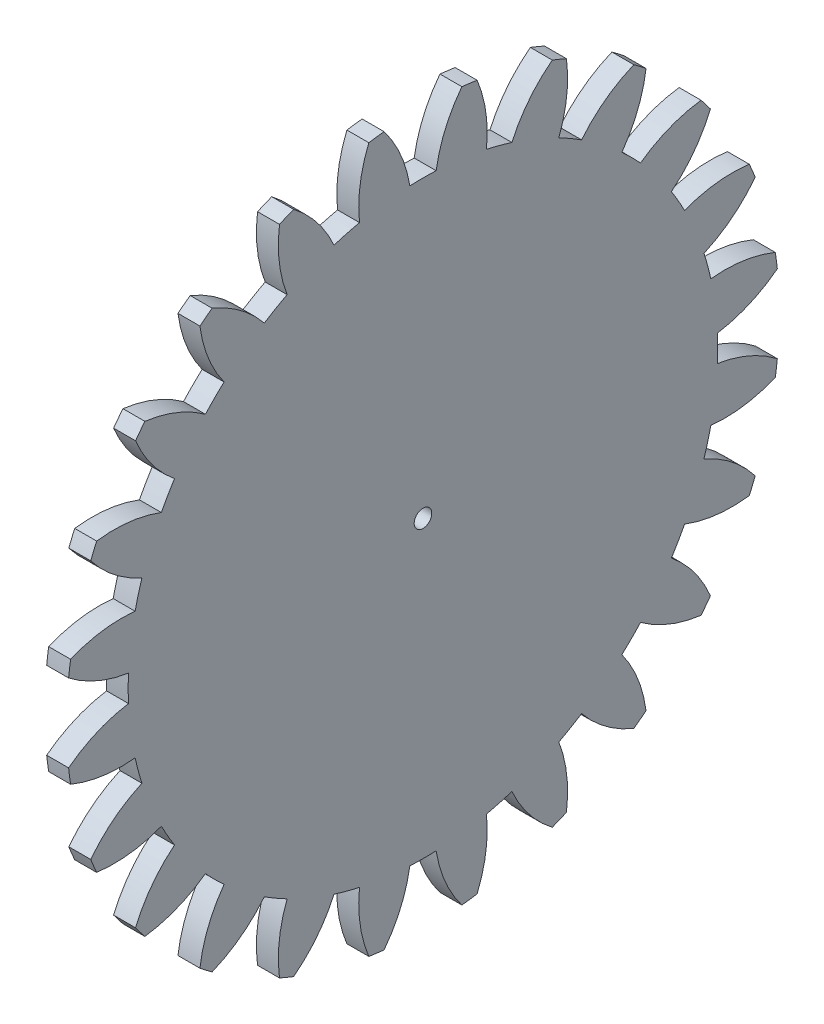
SolidWorks part; units mm, degrees
ref_plane "Plane1" through (0, 0, 0) normal (0, 0, 1) x (1, 0, 0)
ref_plane "Plane2" through (0, 0, 0) normal (0, 1, 0) x (1, 0, 0)
ref_plane "Plane3" through (0, 0, 0) normal (1, 0, 0) x (0, 0, -1)
sketch "HoldingSke" plane through (0, 0, 0) normal (0, 1, 0) x (1, 0, 0)
  line L0 (0, 0) -> (0.7308, -0.3254)
  line L1 (-15, 0) -> (100, 0) construction
  line L2 (0, 0) -> (-2.1039, 2.3779)
  line L3 (0, 0) -> (-11.863, 4.5341)
  line L4 (0, 0) -> (7.8894, 3.5126)
  line L5 (0, 0) -> (-46.8476, -17.4728)
  line L6 (0, 0) -> (-0.829, -0.5593)
  line L7 (-2.1039, 2.3779) -> (8.6587, 51.2062)
  line L8 (-76.2, 54.61) -> (-76.1, 54.61)
  line L9 (-71.009, 38.7566) -> (-53.1078, 45.2721)
  line L10 (-76.2, 71.12) -> (104.1128, 71.12)
  line L11 (0, 0) -> (-1, 0)
  line L12 (-76.2, 101.6) -> (-76.155, 101.6)
  line L13 (24.9733, 27.94) -> (52.9518, 28.4284)
  line L14 (24.9733, 27.94) -> (24.9743, 27.94)
  line L15 (24.9733, 27.94) -> (100.4006, 29.5858)
  line L16 (-63.627, -1.25) -> (-12.827, -1.25)
  circle A0 centre (0, 0) radius 0.4
  circle A1 centre (0, 0) radius 13.4365
  circle A2 centre (0, 0) radius 37.5
  circle A3 centre (0, 0) radius 0.4
  dimension "MHD" = 26.873
  dimension "Hub_dia" = 75
  dimension "Bore" = 0.8
  dimension "MBD" = 0.8
  dimension "Num_teeth" = 24
  dimension "Pitch" = 0.8
  dimension "Overall_len" = 50
  dimension "Show_teeth" = 24
  dimension "Thickness" = 1
  dimension "OAL" = 50.0004
  dimension "T_dim" = 0.1
  dimension "Ap" = 20
  dimension "H" = 19.05
  dimension "Pitch_radius" = 180.3128
  dimension "Width" = 1
  dimension "Backlash" = 0.045
  dimension "Addendum_fac" = 1
  dimension "Dedendum_fac" = 1.25
  dimension "Clearance_fac" = 0.25
  dimension "Dedendum_add" = 0.001
  dimension "Module" = 1.25
sketch "BasProSke" plane through (0, 0, 0) normal (0, 1, 0) x (1, 0, 0)
  line L0 (-10, 0) -> (60, 0) construction
  line L1 (0, 0) -> (0, 16.25)
  line L2 (0, 0) -> (1, 0)
  line L3 (1, 0) -> (1, 16.25)
  line L4 (1, 16.25) -> (0, 16.25)
  dimension "Thickness" = 1
  dimension "Diameter" = 32.5
revolve "Base-Revolve" add sketch "BasProSke" angle 360 about L0
sketch "TooCutSke" plane through (0, 0, 0) normal (1, 0, 0) x (0, 0, -1)
  line L1 (0, 0) -> (0, 107) construction
  line L2 (0, 0) -> (-1.0598, 14.9625) construction
  line L3 (0, 0) -> (-3.9087, 29.6895) construction
  line L4 (-1.0598, 14.9625) -> (-1.9543, 14.8447) construction
  arc A0 (0.6004, 13.4231) -> (-0.6004, 13.4231) centre (0, 0) ccw
  arc A1 (1.7918, 16.1765) -> (-1.7918, 16.1765) centre (0, 0) ccw
  circle A2 centre (0, 0) radius 15 construction
  circle A3 centre (0, 0) radius 14.0954 construction
  arc A4 (-0.6004, 13.4231) -> (-1.7918, 16.1765) centre (-6.5279, 12.4927) ccw
  arc A5 (1.7918, 16.1765) -> (0.6004, 13.4231) centre (6.5279, 12.4927) ccw
  dimension "Root_dia" = 26.873
  dimension "Overcut_dia" = 32.5508
  dimension "Pitch_dia" = 30
  dimension "Base_dia" = 28.1908
  dimension "Flank_rad" = 6
  dimension "Half_ang" = 7.5
  dimension "Half_CT" = 0.9023
extrude "ToothCut" cut sketch "TooCutSke" along normal through all
fillet "Breaks" [suppressed] radius 0.025
fillet "RootFillets" [suppressed] radius 0.3135
pattern_circular "TeethCuts" count 24 over 360 about axis through (0, 0, 0) along (1, 0, 0) of "ToothCut", "RootFillets", "Breaks"
sketch "HubNeaOneSke" plane through (0, 0, 0) normal (-1, 0, 0) x (0, 0, 1)
  circle A0 centre (0, 0) radius 13.4365
  dimension "Diameter" = 26.873
extrude "HubNearOne" [suppressed] add sketch "HubNeaOneSke" along normal blind 49.0004
sketch "HubNeaBotSke" plane through (0, 0, 0) normal (-1, 0, 0) x (0, 0, 1)
  circle A0 centre (0, 0) radius 13.4365
  dimension "Diameter" = 26.873
extrude "HubNearBoth" [suppressed] add sketch "HubNeaBotSke" along normal blind 24.5002
ref_plane "FarPln" through (1, 0, 0) normal (1, 0, 0) x (0, 0, -1)
sketch "HubFarSke" plane through (1, 0, 0) normal (1, 0, 0) x (0, 0, -1)
  circle A0 centre (0, 0) radius 13.4365
  dimension "Diameter" = 26.873
extrude "HubFar" [suppressed] add sketch "HubFarSke" along normal blind 24.5002
sketch "BorSke" plane through (0, 0, 0) normal (1, 0, 0) x (0, 0, -1)
  circle A0 centre (0, 0) radius 0.4
  dimension "Diameter" = 0.8
extrude "Bore" cut sketch "BorSke" along normal mid plane 100.0007
sketch "KeySke" plane through (0, 0, 0) normal (1, 0, 0) x (0, 0, -1)
  line L0 (-0.05, 0) -> (-0.05, 0.5)
  line L1 (-0.05, 0.5) -> (0.05, 0.5)
  line L2 (0.05, 0.5) -> (0.05, 0)
  line L3 (0, 0) -> (0, 34) construction
  line L4 (-0.05, 0) -> (0.05, 0)
  dimension "Offset" = 0.5
extrude "Keyway" [suppressed] cut sketch "KeySke" along normal mid plane 100.0007
pattern_circular "Keyway2" [suppressed] count 2 every 90 about axis through (-10, 0, 0) along (1, 0, 0)
equation "' \"Module@HoldingSke\" = 6.35"
equation "' \"Num_teeth@HoldingSke\" = 12"
equation "' \"Ap@HoldingSke\" =  20"
equation "' \"Ap@HoldingSke\" = 20"
equation "' \"Width@HoldingSke\" = 0.5 * 25.4"
equation "'\"Hub_dia@HoldingSke\"= 1 * 25.4"
equation "'\"Hub_dia@HoldingSke\" = 1 * 25.4"
equation "' \"Overall_len@HoldingSke\" = 1.0 * 25.4"
equation "'\"Bore@HoldingSke\" = 0.5"
equation "' \"T_dim@HoldingSke\" = 0.1 * 25.4"
equation "' \"Width@KeySke\" = 0.25 * 25.4"
equation "' \"Show_teeth@HoldingSke\" = 13"
equation "' \"Backlash@HoldingSke\" = 0.009 * 25.4"
equation "' \"Addendum_fac@HoldingSke\" = 1.0"
equation "' \"Dedendum_fac@HoldingSke\" = 1.25"
equation "' \"Dedendum_add@HoldingSke\" = 0.00005 * 25.4"
equation "' \"Clearance_fac@HoldingSke\" = 0.25"
equation "\"Pitch@HoldingSke\" = 1 / \"Module@HoldingSke\""
equation "\"Overcut_dia@TooCutSke\" = (\"Num_teeth@HoldingSke\" + 2 * \"Addendum_fac@HoldingSke\") / \"Pitch@HoldingSke\" + 0.002 * 25.4"
equation "\"Pitch_dia@TooCutSke\" = \"Num_teeth@HoldingSke\" / \"Pitch@HoldingSke\""
equation "\"Base_dia@TooCutSke\" = \"Num_teeth@HoldingSke\" / \"Pitch@HoldingSke\" * cos((\"Ap@HoldingSke\"  * 3.14159265 / 180))"
equation "\"Root_dia@TooCutSke\" = (\"Num_teeth@HoldingSke\" + 2) / \"Pitch@HoldingSke\" - 2 * (\"Addendum_fac@HoldingSke\" + \"Dedendum_fac@HoldingSke\") / \"Pitch@HoldingSke\" - \"Dedendum_add@HoldingSke\" * 2"
equation "\"Half_ang@TooCutSke\" = 180 / \"Num_teeth@HoldingSke\""
equation "\"Half_CT@TooCutSke\" = \"Num_teeth@HoldingSke\" / \"Pitch@HoldingSke\" * sin((3.14159265 / 2 / \"Num_teeth@HoldingSke\")) / 2 - 7 * \"Backlash@HoldingSke\" / 4"
equation "\"Flank_rad@TooCutSke\" = \"Num_teeth@HoldingSke\" / \"Pitch@HoldingSke\" / 5"
equation "\"Radius@RootFillets\" = \"Clearance_fac@HoldingSke\" / \"Pitch@HoldingSke\" + \"Dedendum_add@HoldingSke\""
equation "\"Break_rad@Breaks\" = 0.02 / \"Pitch@HoldingSke\""
equation "\"Thickness@HoldingSke\" = \"Width@HoldingSke\""
equation "\"OAL@HoldingSke\" = \"Thickness@HoldingSke\""
equation "\"MHD@HoldingSke\" = (\"Num_teeth@HoldingSke\" + 2) / \"Pitch@HoldingSke\" - 2 * (\"Addendum_fac@HoldingSke\" + \"Dedendum_fac@HoldingSke\")  / \"Pitch@HoldingSke\" - \"Dedendum_add@HoldingSke\" * 2"
equation "\"MBD@HoldingSke\" = (\"Num_teeth@HoldingSke\" + 2) / \"Pitch@HoldingSke\" - 2 * (\"Addendum_fac@HoldingSke\" + \"Dedendum_fac@HoldingSke\")  / \"Pitch@HoldingSke\" - \"Dedendum_add@HoldingSke\" * 2 - 0.002 * 25.4"
equation "\"MHD@HoldingSke\" = ((sgn( \"MHD@HoldingSke\" - \"Hub_dia@HoldingSke\" )-1)*( \"MHD@HoldingSke\" - \"Hub_dia@HoldingSke\" ))/-2+ \"Hub_dia@HoldingSke\""
equation "\"MBD@HoldingSke\" = ((sgn( \"MBD@HoldingSke\" - \"Bore@HoldingSke\" )-1)*( \"MBD@HoldingSke\" - \"Bore@HoldingSke\" ))/-2+ \"Bore@HoldingSke\""
equation "\"OAL@HoldingSke\" = ((sgn( \"OAL@HoldingSke\" - \"Overall_len@HoldingSke\" )+1)*( \"OAL@HoldingSke\" - \"Overall_len@HoldingSke\" ))/2 + \"Overall_len@HoldingSke\" + 0.000002 * 25.4"
equation "\"Num_teeth@TeethCuts\" = int( \"Show_teeth@HoldingSke\" ) + 1"
equation "\"Num_teeth@TeethCuts\" = ((sgn( \"Num_teeth@TeethCuts\" - \"Num_teeth@HoldingSke\" )-1)*( \"Num_teeth@TeethCuts\" - \"Num_teeth@HoldingSke\" ))/-2+ \"Num_teeth@HoldingSke\""
equation "\"Num_teeth@TeethCuts\" = ((sgn( \"Num_teeth@TeethCuts\" - 2.0)+1)*( \"Num_teeth@TeethCuts\" - 2.0))/2 +2.0"
equation "\"Angle@TeethCuts\" = 360.0 / \"Num_teeth@HoldingSke\""
equation "\"Diameter@BasProSke\" = (\"Num_teeth@HoldingSke\" + 2 * \"Addendum_fac@HoldingSke\") / \"Pitch@HoldingSke\""
equation "\"Thickness@BasProSke\"  = \"Thickness@HoldingSke\""
equation "' \"Fillet_rad@BasProSke\" =  \"Thickness@HoldingSke\" * 0.05"
equation "' \"Fillet_rad@BasProSke\" = \"Thickness@HoldingSke\" * 0.05"
equation "\"MHD@HoldingSke\" = ((sgn( \"MHD@HoldingSke\" - \"Root_dia@TooCutSke\" )-1)*( \"MHD@HoldingSke\" - \"Root_dia@TooCutSke\" ))/-2+ \"Root_dia@TooCutSke\""
equation "\"Diameter@HubNeaOneSke\" = \"MHD@HoldingSke\""
equation "\"Length@HubNearOne\" = \"OAL@HoldingSke\" - \"Thickness@BasProSke\""
equation "\"Diameter@HubNeaBotSke\" = \"MHD@HoldingSke\""
equation "\"Length@HubNearBoth\" = ( \"OAL@HoldingSke\" - \"Thickness@BasProSke\" ) / 2.0"
equation "\"Thickness@FarPln\" = \"Thickness@BasProSke\""
equation "\"Diameter@HubFarSke\" = \"MHD@HoldingSke\""
equation "\"Length@HubFar\" = ( \"OAL@HoldingSke\" - \"Thickness@BasProSke\" ) / 2.0"
equation "\"Diameter@BorSke\" = \"MBD@HoldingSke\""
equation "\"D1@Bore\" = \"OAL@HoldingSke\" * 2.0"
equation "\"D1@Keyway\" = \"OAL@HoldingSke\" * 2.0"
equation "\"Offset@KeySke\" = \"T_dim@HoldingSke\" + \"MBD@HoldingSke\" / 2.0"
